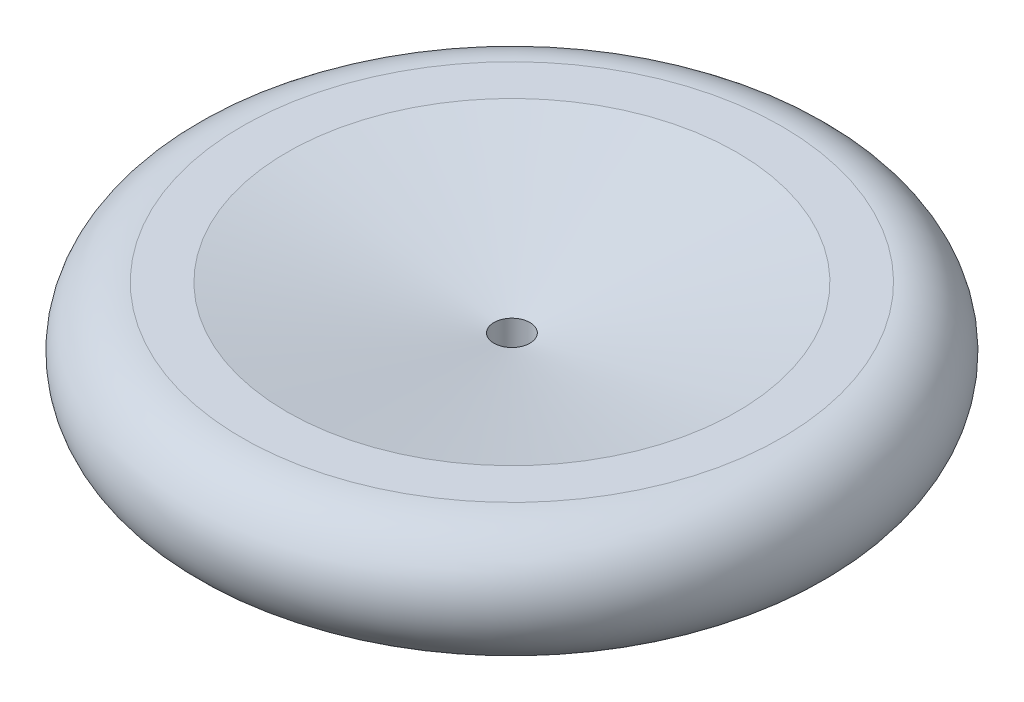
SolidWorks part; units mm, degrees
ref_plane "Front Plane" through (0, 0, 0) normal (0, 0, 1) x (1, 0, 0)
ref_plane "Top Plane" through (0, 0, 0) normal (0, 1, 0) x (1, 0, 0)
ref_plane "Right Plane" through (0, 0, 0) normal (1, 0, 0) x (0, 0, -1)
sketch "Sketch1" plane through (0, 0, 0) normal (0, 0, 1) x (1, 0, 0)
  line L0 (0, 0) -> (60, 0) construction
  line L1 (0, 0) -> (0, 35.6512) construction
  line L2 (4, 0) -> (4, 3.5)
  line L3 (50, 13.2776) -> (60, 13.2776)
  line L4 (4, 3.5) -> (50, 13.2776)
  line L5 (50, -13.2776) -> (60, -13.2776)
  line L6 (4, -3.5) -> (50, -13.2776)
  line L7 (4, -3.5) -> (4, 0)
  arc A0 (60, -13.2776) -> (60, 13.2776) centre (60, 0) ccw
  dimension "D1" = 60
  dimension "D2" = 50
  dimension "D3" = 8
  dimension "D4" = 12
  dimension "D5" = 3.5
revolve "Revolve1" add sketch "Sketch1" angle 360 about L1
